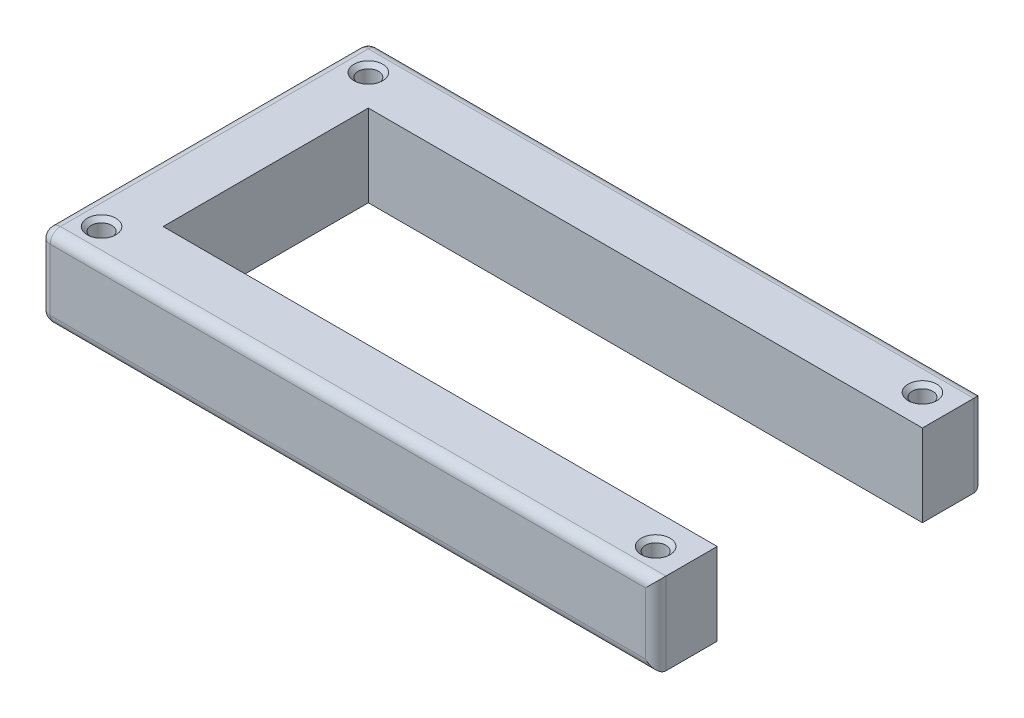
SolidWorks part; units mm, degrees
ref_plane "Front Plane" through (0, 0, 0) normal (0, 0, 1) x (1, 0, 0)
ref_plane "Top Plane" through (0, 0, 0) normal (0, 1, 0) x (1, 0, 0)
ref_plane "Right Plane" through (0, 0, 0) normal (1, 0, 0) x (0, 0, -1)
sketch "Sketch1" plane through (0, 0, 0) normal (0, 1, 0) x (1, 0, 0)
  line L0 (75, 25) -> (75, 40)
  line L1 (75, -40) -> (-75, -40)
  line L2 (75, -40) -> (75, -25)
  line L3 (75, 40) -> (-75, 40)
  line L4 (-75, -40) -> (-75, 40)
  line L5 (75, 25) -> (-60, 25)
  line L7 (75, -25) -> (-60, -25)
  line L8 (-60, 25) -> (-60, -25)
  circle A0 centre (-67.5, 32.5) radius 2.5
  circle A2 centre (67.5, -32.5) radius 2.5
  circle A3 centre (-67.5, -32.5) radius 2.5
  circle A4 centre (67.5, 32.5) radius 2.5
  point P0 (0, 0)
  dimension "D6" = 5
  dimension "D1" = 150
  dimension "D2" = 80
  dimension "D3" = 15
  dimension "D4" = 15
  dimension "D5" = 135
  dimension "D7" = 7.5
  dimension "D8" = 7.5
extrude "Boss-Extrude1" add sketch "Sketch1" along normal blind 20
fillet "Fillet1" radius 2.5 10 edges at (75, 10, -40) (-75, 10, -40) (0, 0, -40) (0, 20, -40) (75, 10, 40) (0, 0, 40) (-75, 0, 0) (-75, 10, 40) (-75, 20, 0) (0, 20, 40)
chamfer "Chamfer1" distance 1 angle 45 4 edges at (67.5, 20, -30) (-67.5, 20, -30) (-67.5, 20, 35) (67.5, 20, 35)
